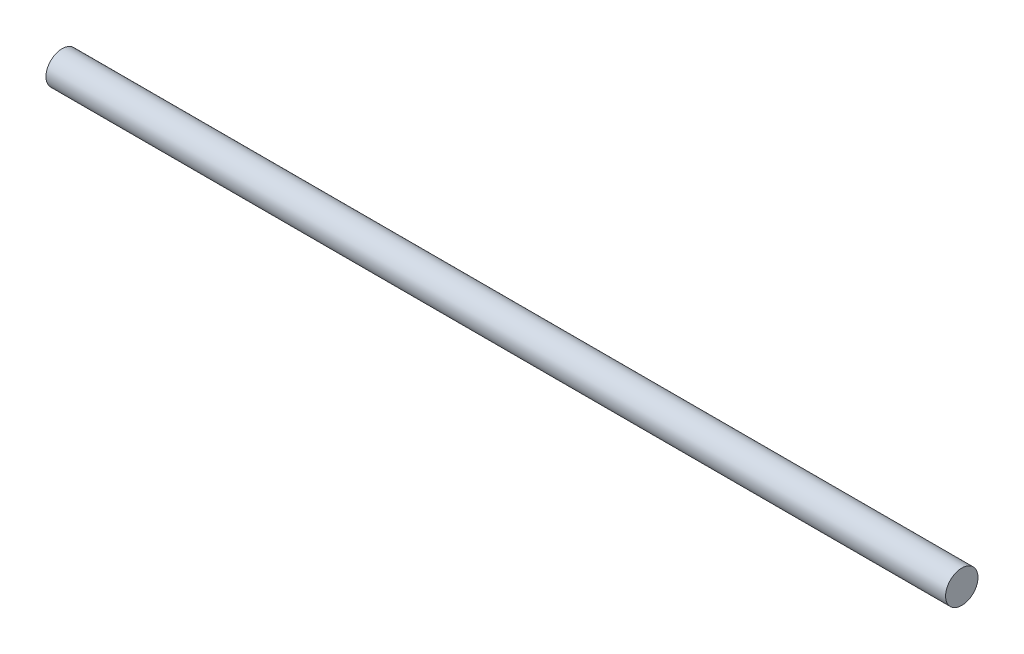
SolidWorks part; units mm, degrees
ref_plane "Front Plane" through (0, 0, 0) normal (0, 0, 1) x (1, 0, 0)
ref_plane "Top Plane" through (0, 0, 0) normal (0, 1, 0) x (1, 0, 0)
ref_plane "Right Plane" through (0, 0, 0) normal (1, 0, 0) x (0, 0, -1)
sketch "Sketch1" plane through (0, 0, 0) normal (1, 0, 0) x (0, 0, -1)
  circle A0 centre (0, 0) radius 4
  dimension "D1" = 8
extrude "Boss-Extrude1" add sketch "Sketch1" along normal blind 222
